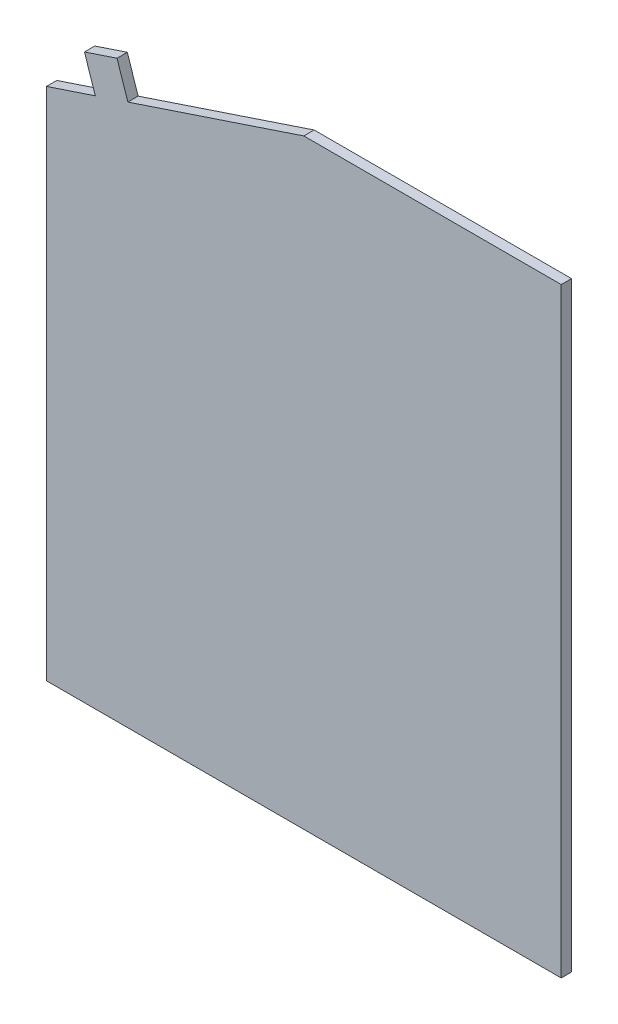
SolidWorks part; units mm, degrees
ref_plane "Plan de face" through (0, 0, 0) normal (0, 0, 1) x (1, 0, 0)
ref_plane "Plan de dessus" through (0, 0, 0) normal (0, 1, 0) x (1, 0, 0)
ref_plane "Plan de droite" through (0, 0, 0) normal (1, 0, 0) x (0, 0, -1)
sketch "Esquisse1" plane through (0, 0, 0) normal (0, 0, 1) x (1, 0, 0)
  line L0 (0, 0) -> (150, 0)
  line L1 (0, 0) -> (0, 150)
  line L2 (0, 150) -> (150, 200) construction
  line L4 (150, 200) -> (150, 0) construction
  line L5 (23.7171, 157.9057) -> (14.2302, 154.7434) construction
  line L6 (23.7171, 157.9057) -> (20.5548, 167.3925)
  line L7 (14.2302, 154.7434) -> (11.068, 164.2302)
  line L8 (20.5548, 167.3925) -> (11.068, 164.2302)
  line L9 (0, 150) -> (14.2302, 154.7434)
  line L10 (23.7171, 157.9057) -> (150, 200) construction
  line L11 (75, 175) -> (150, 175)
  line L12 (23.7171, 157.9057) -> (75, 175)
  line L13 (150, 175) -> (150, 0)
  dimension "D1" = 150
  dimension "D2" = 200
  dimension "D3" = 150
  dimension "D4" = 10
  dimension "D5" = 10
  dimension "D6" = 15
  dimension "D7" = 25
extrude "Boss.-Extru.1" add sketch "Esquisse1" along normal blind 3
